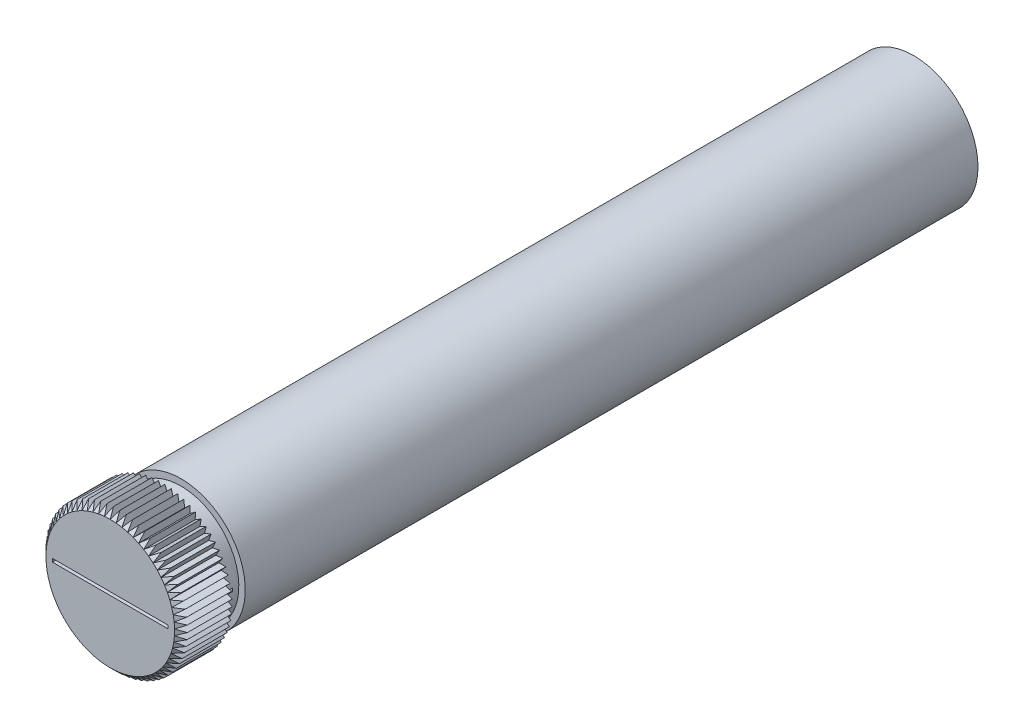
SolidWorks part; units mm, degrees
ref_plane "前视基准面" through (0, 0, 0) normal (0, 0, 1) x (1, 0, 0)
ref_plane "上视基准面" through (0, 0, 0) normal (0, 1, 0) x (1, 0, 0)
ref_plane "右视基准面" through (0, 0, 0) normal (1, 0, 0) x (0, 0, -1)
sketch "草图1" plane through (0, 0, 0) normal (0, 0, 1) x (1, 0, 0)
  circle A0 centre (0, 0) radius 10
  dimension "D1" = 20
extrude "凸台-拉伸1" add sketch "草图1" along normal blind 125
sketch "草图2" plane through (0, 0, 125) normal (0, 0, 1) x (1, 0, 0)
  circle A0 centre (0, 0) radius 11
  dimension "D1" = 22
extrude "凸台-拉伸2" add sketch "草图2" against normal blind 8
chamfer "倒角1" distance 1 angle 45 1 edges at (11, 0, 125)
sketch "草图3" plane through (0, 0, 125) normal (0, 0, 1) x (1, 0, 0)
  line L0 (0, 0) -> (0, 15.9276) construction
  line L1 (0, 11.3) -> (-0.5, 10.9886)
  line L2 (-0.5, 10.9886) -> (0, 10)
  line L3 (0.5, 10.9886) -> (0, 10)
  line L4 (0, 11.3) -> (0.5, 10.9886)
  line L5 (1.4972, 10.8976) -> (0.9093, 9.9586)
  line L6 (1.0276, 11.2532) -> (1.4972, 10.8976)
  line L7 (1.0276, 11.2532) -> (0.5013, 10.9886)
  line L8 (0.5013, 10.9886) -> (0.9093, 9.9586)
  line L9 (2.4819, 10.7163) -> (1.8112, 9.8346)
  line L10 (2.0466, 11.1131) -> (2.4819, 10.7163)
  line L11 (2.0466, 11.1131) -> (1.4985, 10.8975)
  line L12 (1.4985, 10.8975) -> (1.8112, 9.8346)
  line L13 (3.4462, 10.4462) -> (2.698, 9.6292)
  line L14 (3.0487, 10.881) -> (3.4462, 10.4462)
  line L15 (3.0487, 10.881) -> (2.4832, 10.716)
  line L16 (2.4832, 10.716) -> (2.698, 9.6292)
  line L17 (4.3818, 10.0896) -> (3.5624, 9.3439)
  line L18 (4.0255, 10.5587) -> (4.3818, 10.0896)
  line L19 (4.0255, 10.5587) -> (3.4474, 10.4458)
  line L20 (3.4474, 10.4458) -> (3.5624, 9.3439)
  line L21 (5.2811, 9.6493) -> (4.3973, 8.9813)
  line L22 (4.969, 10.1488) -> (5.2811, 9.6493)
  line L23 (4.969, 10.1488) -> (4.383, 10.0891)
  line L24 (4.383, 10.0891) -> (4.3973, 8.9813)
  line L25 (6.1367, 9.1291) -> (5.1958, 8.5442)
  line L26 (5.8713, 9.6549) -> (6.1367, 9.1291)
  line L27 (5.8713, 9.6549) -> (5.2823, 9.6487)
  line L28 (5.2823, 9.6487) -> (5.1958, 8.5442)
  line L29 (6.9415, 8.5332) -> (5.9513, 8.0363)
  line L30 (6.7249, 9.081) -> (6.9415, 8.5332)
  line L31 (6.7249, 9.081) -> (6.1378, 9.1284)
  line L32 (6.1378, 9.1284) -> (5.9513, 8.0363)
  line L33 (7.6887, 7.8667) -> (6.6574, 7.4618)
  line L34 (7.5229, 8.4319) -> (7.6887, 7.8667)
  line L35 (7.5229, 8.4319) -> (6.9425, 8.5324)
  line L36 (6.9425, 8.5324) -> (6.6574, 7.4618)
  line L37 (8.3722, 7.1349) -> (7.3084, 6.8255)
  line L38 (8.2584, 7.7129) -> (8.3722, 7.1349)
  line L39 (8.2584, 7.7129) -> (7.6896, 7.8657)
  line L40 (7.6896, 7.8657) -> (7.3084, 6.8255)
  line L41 (8.9863, 6.344) -> (7.8988, 6.1327)
  line L42 (8.9256, 6.9299) -> (8.9863, 6.344)
  line L43 (8.9256, 6.9299) -> (8.373, 7.1339)
  line L44 (8.373, 7.1339) -> (7.8988, 6.1327)
  line L45 (9.5259, 5.5006) -> (8.4237, 5.389)
  line L46 (9.5188, 6.0896) -> (9.5259, 5.5006)
  line L47 (9.5188, 6.0896) -> (8.9871, 6.3429)
  line L48 (8.9871, 6.3429) -> (8.4237, 5.389)
  line L49 (9.9867, 4.6115) -> (8.8789, 4.6007)
  line L50 (10.0331, 5.1987) -> (9.9867, 4.6115)
  line L51 (10.0331, 5.1987) -> (9.5266, 5.4994)
  line L52 (9.5266, 5.4994) -> (8.8789, 4.6007)
  line L53 (10.3646, 3.6843) -> (9.2604, 3.7742)
  line L54 (10.4643, 4.2648) -> (10.3646, 3.6843)
  line L55 (10.4643, 4.2648) -> (9.9872, 4.6103)
  line L56 (9.9872, 4.6103) -> (9.2604, 3.7742)
  line L57 (10.6567, 2.7265) -> (9.5653, 2.9165)
  line L58 (10.8087, 3.2956) -> (10.6567, 2.7265)
  line L59 (10.8087, 3.2956) -> (10.3651, 3.6831)
  line L60 (10.3651, 3.6831) -> (9.5653, 2.9165)
  line L61 (10.8605, 1.7462) -> (9.7908, 2.0346)
  line L62 (11.0637, 2.2991) -> (10.8605, 1.7462)
  line L63 (11.0637, 2.2991) -> (10.6571, 2.7252)
  line L64 (10.6571, 2.7252) -> (9.7908, 2.0346)
  line L65 (10.9743, 0.7513) -> (9.9353, 1.1358)
  line L66 (11.2269, 1.2835) -> (10.9743, 0.7513)
  line L67 (11.2269, 1.2835) -> (10.8607, 1.7449)
  line L68 (10.8607, 1.7449) -> (9.9353, 1.1358)
  line L69 (10.9972, -0.2497) -> (9.9974, 0.2276)
  line L70 (11.2971, 0.2572) -> (10.9972, -0.2497)
  line L71 (11.2971, 0.2572) -> (10.9744, 0.75)
  line L72 (10.9744, 0.75) -> (9.9974, 0.2276)
  line L73 (10.9289, -1.2487) -> (9.9767, -0.6824)
  line L74 (11.2737, -0.7711) -> (10.9289, -1.2487)
  line L75 (11.2737, -0.7711) -> (10.9971, -0.2511)
  line L76 (10.9971, -0.2511) -> (9.9767, -0.6824)
  line L77 (10.7701, -2.2374) -> (9.8733, -1.5868)
  line L78 (11.1568, -1.7931) -> (10.7701, -2.2374)
  line L79 (11.1568, -1.7931) -> (10.9287, -1.25)
  line L80 (10.9287, -1.25) -> (9.8733, -1.5868)
  line L81 (10.522, -3.2075) -> (9.6881, -2.4781)
  line L82 (10.9475, -2.8002) -> (10.522, -3.2075)
  line L83 (10.9475, -2.8002) -> (10.7698, -2.2387)
  line L84 (10.7698, -2.2387) -> (9.6881, -2.4781)
  line L85 (10.1867, -4.151) -> (9.4226, -3.3488)
  line L86 (10.6475, -3.7841) -> (10.1867, -4.151)
  line L87 (10.6475, -3.7841) -> (10.5216, -3.2087)
  line L88 (10.5216, -3.2087) -> (9.4226, -3.3488)
  line L89 (9.767, -5.0601) -> (9.079, -4.1918)
  line L90 (10.2593, -4.7367) -> (9.767, -5.0601)
  line L91 (10.2593, -4.7367) -> (10.1862, -4.1522)
  line L92 (10.1862, -4.1522) -> (9.079, -4.1918)
  line L93 (9.2664, -5.9273) -> (8.6603, -5)
  line L94 (9.7861, -5.65) -> (9.2664, -5.9273)
  line L95 (9.7861, -5.65) -> (9.7664, -5.0613)
  line L96 (9.7664, -5.0613) -> (8.6603, -5)
  line L97 (8.689, -6.7454) -> (8.1697, -5.7668)
  line L98 (9.2318, -6.5165) -> (8.689, -6.7454)
  line L99 (9.2318, -6.5165) -> (9.2657, -5.9284)
  line L100 (9.2657, -5.9284) -> (8.1697, -5.7668)
  line L101 (8.0396, -7.5076) -> (7.6114, -6.4858)
  line L102 (8.6009, -7.329) -> (8.0396, -7.5076)
  line L103 (8.6009, -7.329) -> (8.6882, -6.7465)
  line L104 (8.6882, -6.7465) -> (7.6114, -6.4858)
  line L105 (7.3236, -8.2076) -> (6.9901, -7.1511)
  line L106 (7.8988, -8.0807) -> (7.3236, -8.2076)
  line L107 (7.8988, -8.0807) -> (8.0387, -7.5086)
  line L108 (8.0387, -7.5086) -> (6.9901, -7.1511)
  line L109 (6.5469, -8.8395) -> (6.3109, -7.7571)
  line L110 (7.1313, -8.7655) -> (6.5469, -8.8395)
  line L111 (7.1313, -8.7655) -> (7.3226, -8.2085)
  line L112 (7.3226, -8.2085) -> (6.3109, -7.7571)
  line L113 (5.716, -9.3983) -> (5.5793, -8.2989)
  line L114 (6.3047, -9.3777) -> (5.716, -9.3983)
  line L115 (6.3047, -9.3777) -> (6.5459, -8.8403)
  line L116 (6.5459, -8.8403) -> (5.5793, -8.2989)
  line L117 (4.8377, -9.8791) -> (4.8016, -8.7718)
  line L118 (5.4258, -9.9122) -> (4.8377, -9.8791)
  line L119 (5.4258, -9.9122) -> (5.7149, -9.399)
  line L120 (5.7149, -9.399) -> (4.8016, -8.7718)
  line L121 (3.9193, -10.2781) -> (3.984, -9.1721)
  line L122 (4.5019, -10.3645) -> (3.9193, -10.2781)
  line L123 (4.5019, -10.3645) -> (4.8365, -9.8797)
  line L124 (4.8365, -9.8797) -> (3.984, -9.1721)
  line L125 (2.9684, -10.5919) -> (3.1334, -9.4964)
  line L126 (3.5408, -10.7309) -> (2.9684, -10.5919)
  line L127 (3.5408, -10.7309) -> (3.918, -10.2786)
  line L128 (3.918, -10.2786) -> (3.1334, -9.4964)
  line L129 (1.9929, -10.818) -> (2.2569, -9.742)
  line L130 (2.5503, -11.0084) -> (1.9929, -10.818)
  line L131 (2.5503, -11.0084) -> (2.9671, -10.5923)
  line L132 (2.9671, -10.5923) -> (2.2569, -9.742)
  line L133 (1.0009, -10.9544) -> (1.3617, -9.9069)
  line L134 (1.5387, -11.1948) -> (1.0009, -10.9544)
  line L135 (1.5387, -11.1948) -> (1.9916, -10.8182)
  line L136 (1.9916, -10.8182) -> (1.3617, -9.9069)
  line L137 (0.0007, -11) -> (0.4551, -9.9896)
  line L138 (0.5143, -11.2883) -> (0.0007, -11)
  line L139 (0.5143, -11.2883) -> (0.9996, -10.9545)
  line L140 (0.9996, -10.9545) -> (0.4551, -9.9896)
  line L141 (-0.9996, -10.9545) -> (-0.4551, -9.9896)
  line L142 (-0.5143, -11.2883) -> (-0.9996, -10.9545)
  line L143 (-0.5143, -11.2883) -> (-0.0007, -11)
  line L144 (-0.0007, -11) -> (-0.4551, -9.9896)
  line L145 (-1.9916, -10.8182) -> (-1.3617, -9.9069)
  line L146 (-1.5387, -11.1948) -> (-1.9916, -10.8182)
  line L147 (-1.5387, -11.1948) -> (-1.0009, -10.9544)
  line L148 (-1.0009, -10.9544) -> (-1.3617, -9.9069)
  line L149 (-2.9671, -10.5923) -> (-2.2569, -9.742)
  line L150 (-2.5503, -11.0084) -> (-2.9671, -10.5923)
  line L151 (-2.5503, -11.0084) -> (-1.9929, -10.818)
  line L152 (-1.9929, -10.818) -> (-2.2569, -9.742)
  line L153 (-3.918, -10.2786) -> (-3.1334, -9.4964)
  line L154 (-3.5408, -10.7309) -> (-3.918, -10.2786)
  line L155 (-3.5408, -10.7309) -> (-2.9684, -10.5919)
  line L156 (-2.9684, -10.5919) -> (-3.1334, -9.4964)
  line L157 (-4.8365, -9.8797) -> (-3.984, -9.1721)
  line L158 (-4.5019, -10.3645) -> (-4.8365, -9.8797)
  line L159 (-4.5019, -10.3645) -> (-3.9193, -10.2781)
  line L160 (-3.9193, -10.2781) -> (-3.984, -9.1721)
  line L161 (-5.7149, -9.399) -> (-4.8016, -8.7718)
  line L162 (-5.4258, -9.9122) -> (-5.7149, -9.399)
  line L163 (-5.4258, -9.9122) -> (-4.8377, -9.8791)
  line L164 (-4.8377, -9.8791) -> (-4.8016, -8.7718)
  line L165 (-6.5459, -8.8403) -> (-5.5793, -8.2989)
  line L166 (-6.3047, -9.3777) -> (-6.5459, -8.8403)
  line L167 (-6.3047, -9.3777) -> (-5.716, -9.3983)
  line L168 (-5.716, -9.3983) -> (-5.5793, -8.2989)
  line L169 (-7.3226, -8.2085) -> (-6.3109, -7.7571)
  line L170 (-7.1313, -8.7655) -> (-7.3226, -8.2085)
  line L171 (-7.1313, -8.7655) -> (-6.5469, -8.8395)
  line L172 (-6.5469, -8.8395) -> (-6.3109, -7.7571)
  line L173 (-8.0387, -7.5086) -> (-6.9901, -7.1511)
  line L174 (-7.8988, -8.0807) -> (-8.0387, -7.5086)
  line L175 (-7.8988, -8.0807) -> (-7.3236, -8.2076)
  line L176 (-7.3236, -8.2076) -> (-6.9901, -7.1511)
  line L177 (-8.6882, -6.7465) -> (-7.6114, -6.4858)
  line L178 (-8.6009, -7.329) -> (-8.6882, -6.7465)
  line L179 (-8.6009, -7.329) -> (-8.0396, -7.5076)
  line L180 (-8.0396, -7.5076) -> (-7.6114, -6.4858)
  line L181 (-9.2657, -5.9284) -> (-8.1697, -5.7668)
  line L182 (-9.2318, -6.5165) -> (-9.2657, -5.9284)
  line L183 (-9.2318, -6.5165) -> (-8.689, -6.7454)
  line L184 (-8.689, -6.7454) -> (-8.1697, -5.7668)
  line L185 (-9.7664, -5.0613) -> (-8.6603, -5)
  line L186 (-9.7861, -5.65) -> (-9.7664, -5.0613)
  line L187 (-9.7861, -5.65) -> (-9.2664, -5.9273)
  line L188 (-9.2664, -5.9273) -> (-8.6603, -5)
  line L189 (-10.1862, -4.1522) -> (-9.079, -4.1918)
  line L190 (-10.2593, -4.7367) -> (-10.1862, -4.1522)
  line L191 (-10.2593, -4.7367) -> (-9.767, -5.0601)
  line L192 (-9.767, -5.0601) -> (-9.079, -4.1918)
  line L193 (-10.5216, -3.2087) -> (-9.4226, -3.3488)
  line L194 (-10.6475, -3.7841) -> (-10.5216, -3.2087)
  line L195 (-10.6475, -3.7841) -> (-10.1867, -4.151)
  line L196 (-10.1867, -4.151) -> (-9.4226, -3.3488)
  line L197 (-10.7698, -2.2387) -> (-9.6881, -2.4781)
  line L198 (-10.9475, -2.8002) -> (-10.7698, -2.2387)
  line L199 (-10.9475, -2.8002) -> (-10.522, -3.2075)
  line L200 (-10.522, -3.2075) -> (-9.6881, -2.4781)
  line L201 (-10.9287, -1.25) -> (-9.8733, -1.5868)
  line L202 (-11.1568, -1.7931) -> (-10.9287, -1.25)
  line L203 (-11.1568, -1.7931) -> (-10.7701, -2.2374)
  line L204 (-10.7701, -2.2374) -> (-9.8733, -1.5868)
  line L205 (-10.9971, -0.2511) -> (-9.9767, -0.6824)
  line L206 (-11.2737, -0.7711) -> (-10.9971, -0.2511)
  line L207 (-11.2737, -0.7711) -> (-10.9289, -1.2487)
  line L208 (-10.9289, -1.2487) -> (-9.9767, -0.6824)
  line L209 (-10.9744, 0.75) -> (-9.9974, 0.2276)
  line L210 (-11.2971, 0.2572) -> (-10.9744, 0.75)
  line L211 (-11.2971, 0.2572) -> (-10.9972, -0.2497)
  line L212 (-10.9972, -0.2497) -> (-9.9974, 0.2276)
  line L213 (-10.8607, 1.7449) -> (-9.9353, 1.1358)
  line L214 (-11.2269, 1.2835) -> (-10.8607, 1.7449)
  line L215 (-11.2269, 1.2835) -> (-10.9743, 0.7513)
  line L216 (-10.9743, 0.7513) -> (-9.9353, 1.1358)
  line L217 (-10.6571, 2.7252) -> (-9.7908, 2.0346)
  line L218 (-11.0637, 2.2991) -> (-10.6571, 2.7252)
  line L219 (-11.0637, 2.2991) -> (-10.8605, 1.7462)
  line L220 (-10.8605, 1.7462) -> (-9.7908, 2.0346)
  line L221 (-10.3651, 3.6831) -> (-9.5653, 2.9165)
  line L222 (-10.8087, 3.2956) -> (-10.3651, 3.6831)
  line L223 (-10.8087, 3.2956) -> (-10.6567, 2.7265)
  line L224 (-10.6567, 2.7265) -> (-9.5653, 2.9165)
  line L225 (-9.9872, 4.6103) -> (-9.2604, 3.7742)
  line L226 (-10.4643, 4.2648) -> (-9.9872, 4.6103)
  line L227 (-10.4643, 4.2648) -> (-10.3646, 3.6843)
  line L228 (-10.3646, 3.6843) -> (-9.2604, 3.7742)
  line L229 (-9.5266, 5.4994) -> (-8.8789, 4.6007)
  line L230 (-10.0331, 5.1987) -> (-9.5266, 5.4994)
  line L231 (-10.0331, 5.1987) -> (-9.9867, 4.6115)
  line L232 (-9.9867, 4.6115) -> (-8.8789, 4.6007)
  line L233 (-8.9871, 6.3429) -> (-8.4237, 5.389)
  line L234 (-9.5188, 6.0896) -> (-8.9871, 6.3429)
  line L235 (-9.5188, 6.0896) -> (-9.5259, 5.5006)
  line L236 (-9.5259, 5.5006) -> (-8.4237, 5.389)
  line L237 (-8.373, 7.1339) -> (-7.8988, 6.1327)
  line L238 (-8.9256, 6.9299) -> (-8.373, 7.1339)
  line L239 (-8.9256, 6.9299) -> (-8.9863, 6.344)
  line L240 (-8.9863, 6.344) -> (-7.8988, 6.1327)
  line L241 (-7.6896, 7.8657) -> (-7.3084, 6.8255)
  line L242 (-8.2584, 7.7129) -> (-7.6896, 7.8657)
  line L243 (-8.2584, 7.7129) -> (-8.3722, 7.1349)
  line L244 (-8.3722, 7.1349) -> (-7.3084, 6.8255)
  line L245 (-6.9425, 8.5324) -> (-6.6574, 7.4618)
  line L246 (-7.5229, 8.4319) -> (-6.9425, 8.5324)
  line L247 (-7.5229, 8.4319) -> (-7.6887, 7.8667)
  line L248 (-7.6887, 7.8667) -> (-6.6574, 7.4618)
  line L249 (-6.1378, 9.1284) -> (-5.9513, 8.0363)
  line L250 (-6.7249, 9.081) -> (-6.1378, 9.1284)
  line L251 (-6.7249, 9.081) -> (-6.9415, 8.5332)
  line L252 (-6.9415, 8.5332) -> (-5.9513, 8.0363)
  line L253 (-5.2823, 9.6487) -> (-5.1958, 8.5442)
  line L254 (-5.8713, 9.6549) -> (-5.2823, 9.6487)
  line L255 (-5.8713, 9.6549) -> (-6.1367, 9.1291)
  line L256 (-6.1367, 9.1291) -> (-5.1958, 8.5442)
  line L257 (-4.383, 10.0891) -> (-4.3973, 8.9813)
  line L258 (-4.969, 10.1488) -> (-4.383, 10.0891)
  line L259 (-4.969, 10.1488) -> (-5.2811, 9.6493)
  line L260 (-5.2811, 9.6493) -> (-4.3973, 8.9813)
  line L261 (-3.4474, 10.4458) -> (-3.5624, 9.3439)
  line L262 (-4.0255, 10.5587) -> (-3.4474, 10.4458)
  line L263 (-4.0255, 10.5587) -> (-4.3818, 10.0896)
  line L264 (-4.3818, 10.0896) -> (-3.5624, 9.3439)
  line L265 (-2.4832, 10.716) -> (-2.698, 9.6292)
  line L266 (-3.0487, 10.881) -> (-2.4832, 10.716)
  line L267 (-3.0487, 10.881) -> (-3.4462, 10.4462)
  line L268 (-3.4462, 10.4462) -> (-2.698, 9.6292)
  line L269 (-1.4985, 10.8975) -> (-1.8112, 9.8346)
  line L270 (-2.0466, 11.1131) -> (-1.4985, 10.8975)
  line L271 (-2.0466, 11.1131) -> (-2.4819, 10.7163)
  line L272 (-2.4819, 10.7163) -> (-1.8112, 9.8346)
  line L273 (-0.5013, 10.9886) -> (-0.9093, 9.9586)
  line L274 (-1.0276, 11.2532) -> (-0.5013, 10.9886)
  line L275 (-1.0276, 11.2532) -> (-1.4972, 10.8976)
  line L276 (-1.4972, 10.8976) -> (-0.9093, 9.9586)
  circle A0 centre (0, 0) radius 11 construction
  circle A1 centre (0, 0) radius 10 construction
  dimension "D1" = 0.5
  dimension "D2" = 69
  dimension "D3" = 1.3
extrude "切除-拉伸1" cut sketch "草图3" against normal up to next (8 mm away)
sketch "草图4" plane through (0, 0, 117) normal (0, 0, -1) x (-1, 0, 0)
  circle A0 centre (0, 0) radius 9
  circle A1 centre (0, 0) radius 10
  dimension "D1" = 18
  dimension "D2" = 20
extrude "切除-拉伸2" cut sketch "草图4" along normal blind 3
sketch "草图5" plane through (0, 0, 125) normal (0, 0, 1) x (1, 0, 0)
  line L1 (9, 0.25) -> (-9, 0.25)
  line L2 (9, 0.25) -> (9, -0.25)
  line L3 (9, -0.25) -> (-9, -0.25)
  line L4 (-9, 0.25) -> (-9, -0.25)
  line L5 (9, 0.25) -> (-9, -0.25) construction
  line L6 (9, -0.25) -> (-9, 0.25) construction
  point P0 (0, 0)
  dimension "D1" = 18
  dimension "D2" = 0.5
extrude "切除-拉伸3" cut sketch "草图5" against normal blind 10
